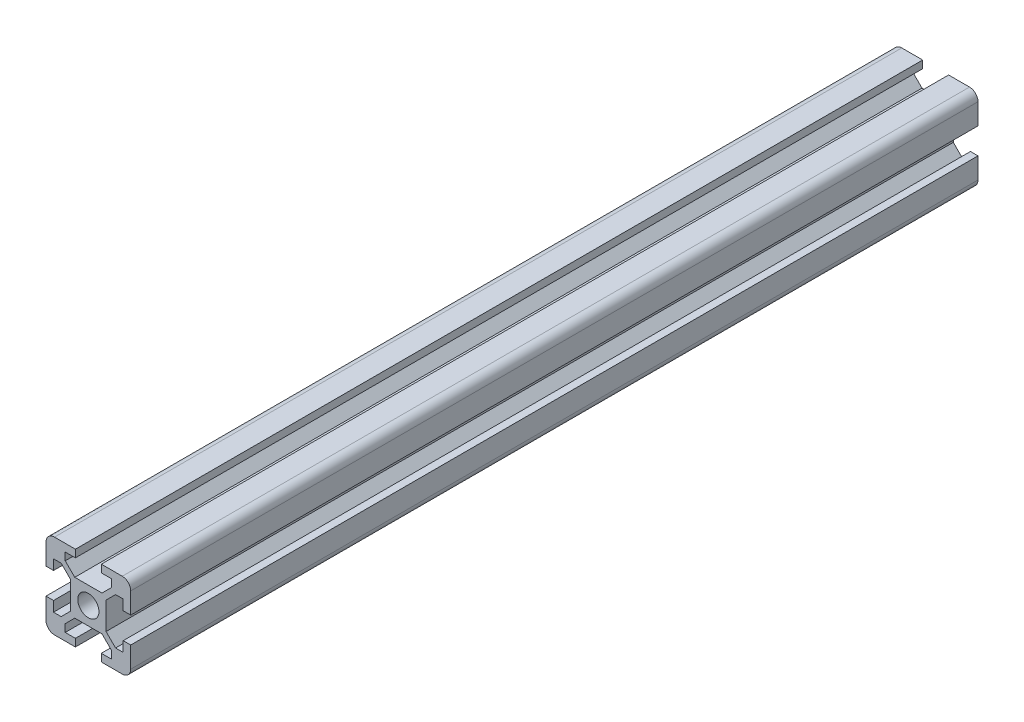
SolidWorks part; units mm, degrees
material "1060 Alloy"
ref_plane "Front Plane" through (0, 0, 0) normal (0, 0, 1) x (1, 0, 0)
ref_plane "Top Plane" through (0, 0, 0) normal (0, 1, 0) x (1, 0, 0)
ref_plane "Right Plane" through (0, 0, 0) normal (1, 0, 0) x (0, 0, -1)
sketch "Sketch1" plane through (0, 0, 0) normal (0, 0, 1) x (1, 0, 0)
  line L0 (-5.46, -6.42) -> (-3.215, -4.175)
  line L1 (-10, -10) -> (-3.06, -10)
  line L2 (-10, -10) -> (-10, -3.06)
  line L3 (-10, 10) -> (-3.06, 10)
  line L4 (10, -10) -> (10, -3.06)
  line L5 (-10, -10) -> (10, 10) construction
  line L6 (-10, 10) -> (10, -10) construction
  line L7 (-3.215, -4.175) -> (3.215, -4.175)
  line L8 (-4.175, -3.215) -> (-4.175, 3.215)
  line L9 (-3.215, 4.175) -> (3.215, 4.175)
  line L10 (4.175, -3.215) -> (4.175, 3.215)
  line L11 (-4.175, -4.175) -> (4.175, 4.175) construction
  line L12 (-4.175, 4.175) -> (4.175, -4.175) construction
  line L13 (-5.46, 6.42) -> (-5.46, 8.22)
  line L14 (-5.46, 8.22) -> (-3.06, 8.22)
  line L15 (-3.06, 8.22) -> (-3.06, 10)
  line L16 (-6.42, -5.46) -> (-4.175, -3.215)
  line L17 (5.46, 6.42) -> (5.46, 8.22)
  line L18 (5.46, 8.22) -> (3.06, 8.22)
  line L19 (3.06, 8.22) -> (3.06, 10)
  line L20 (-5.46, 6.42) -> (-3.215, 4.175)
  line L21 (6.42, 5.46) -> (8.22, 5.46)
  line L22 (8.22, 5.46) -> (8.22, 3.06)
  line L23 (8.22, 3.06) -> (10, 3.06)
  line L24 (8.22, -5.46) -> (6.42, -5.46)
  line L25 (-6.42, 5.46) -> (-4.175, 3.215)
  line L26 (8.22, -5.46) -> (8.22, -3.06)
  line L27 (8.22, -3.06) -> (10, -3.06)
  line L28 (5.46, 6.42) -> (3.215, 4.175)
  line L29 (5.46, -6.42) -> (5.46, -8.22)
  line L30 (5.46, -8.22) -> (3.06, -8.22)
  line L31 (3.06, -8.22) -> (3.06, -10)
  line L32 (6.42, 5.46) -> (4.175, 3.215)
  line L33 (-6.42, 5.46) -> (-8.22, 5.46)
  line L34 (-8.22, 5.46) -> (-8.22, 3.06)
  line L35 (-8.22, 3.06) -> (-10, 3.06)
  line L36 (6.42, -5.46) -> (4.175, -3.215)
  line L37 (-6.42, -5.46) -> (-8.22, -5.46)
  line L38 (-8.22, -5.46) -> (-8.22, -3.06)
  line L39 (-8.22, -3.06) -> (-10, -3.06)
  line L40 (5.46, -6.42) -> (3.215, -4.175)
  line L41 (-5.46, -6.42) -> (-5.46, -8.22)
  line L42 (-5.46, -8.22) -> (-3.06, -8.22)
  line L43 (-3.06, -8.22) -> (-3.06, -10)
  line L44 (-10, 3.06) -> (-10, 10)
  line L45 (3.06, 10) -> (10, 10)
  line L46 (10, 3.06) -> (10, 10)
  line L47 (3.06, -10) -> (10, -10)
  circle A0 centre (0, 0) radius 2.5
  point P0 (0, 0)
  dimension "D3" = 5
  dimension "D1" = 20
  dimension "D2" = 20
  dimension "D4" = 8.35
  dimension "D5" = 8.35
  dimension "D6" = 6.94
  dimension "D7" = 1.78
  dimension "D8" = 2.4
  dimension "D9" = 1.8
extrude "Boss-Extrude1" add sketch "Sketch1" along normal blind 200
fillet "Fillet1" radius 2 4 edges at (-10, -10, 100) (10, -10, 100) (-10, 10, 100) (10, 10, 100)
ref_plane "Plane1" through (0, 0, -70) normal (0, 0, 1) x (1, 0, 0)
ref_plane "Plane2" through (0, 0, 0) normal (1, 0, 0) x (0, 0, -1)
ref_plane "Plane3" through (0, 0, 0) normal (0, 1, 0) x (1, 0, 0)
ref_plane "Plane4" through (0, 0, 100) normal (0, 0, 1) x (1, 0, 0)
